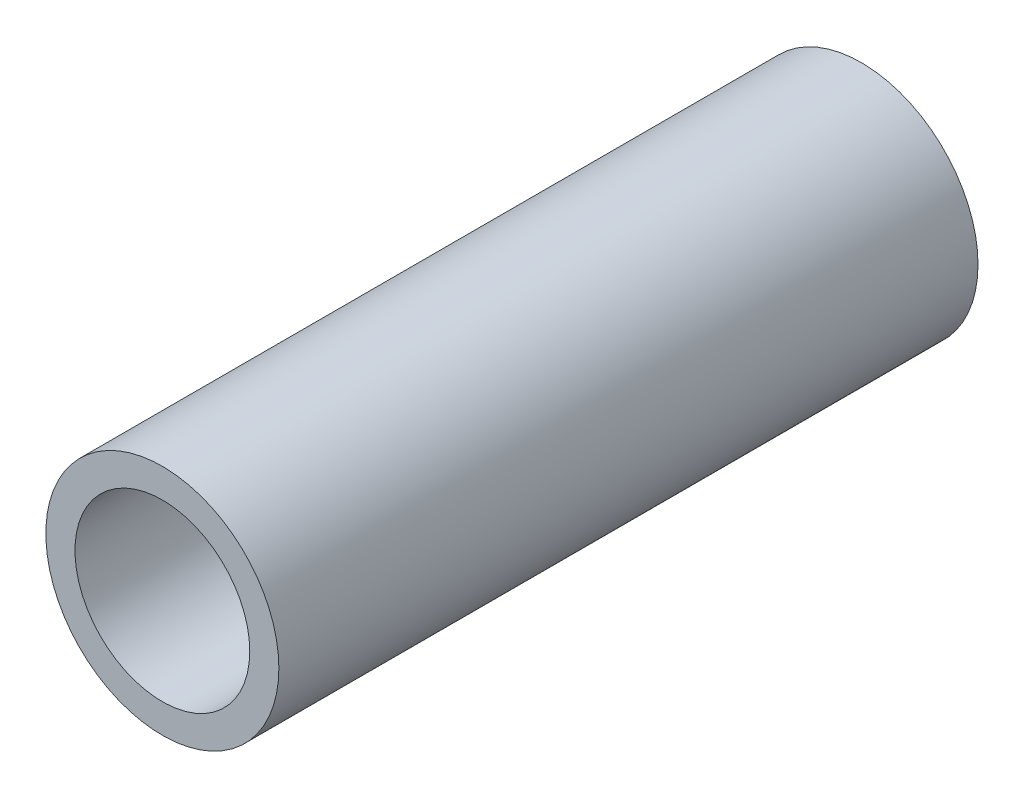
SolidWorks part; units mm, degrees
ref_plane "Front Plane" through (0, 0, 0) normal (0, 0, 1) x (1, 0, 0)
ref_plane "Top Plane" through (0, 0, 0) normal (0, 1, 0) x (1, 0, 0)
ref_plane "Right Plane" through (0, 0, 0) normal (1, 0, 0) x (0, 0, -1)
sketch "Sketch1" plane through (0, 0, 0) normal (0, 0, 1) x (1, 0, 0)
  circle A0 centre (0, 0) radius 3
  circle A1 centre (0, 0) radius 4
  dimension "D1" = 8
  dimension "D2" = 6
extrude "Boss-Extrude1" add sketch "Sketch1" along normal blind 24
